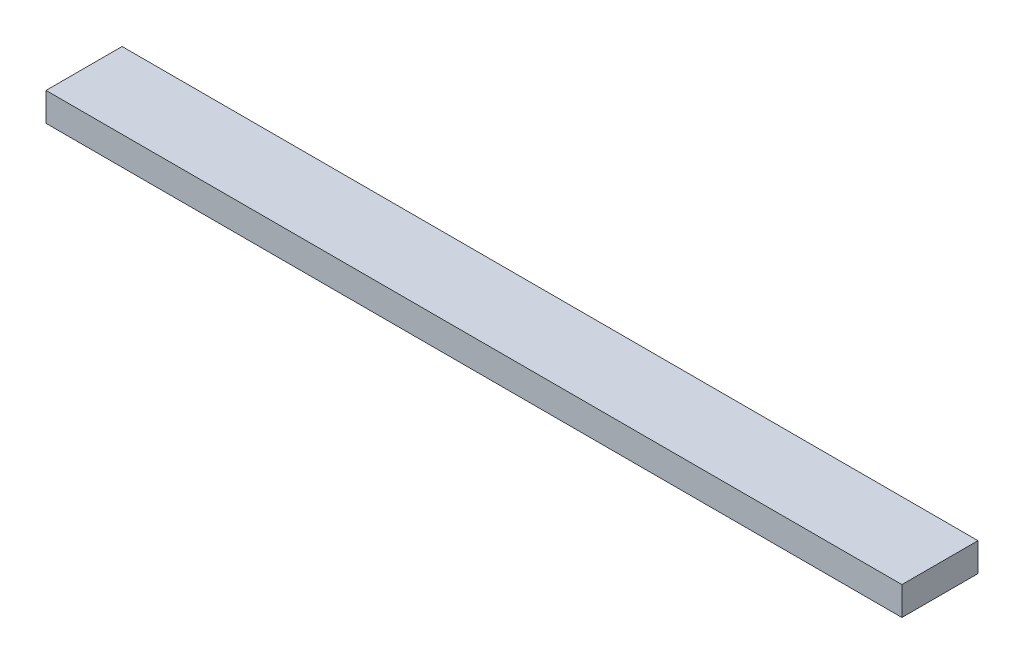
SolidWorks part; units mm, degrees
ref_plane "Front Plane" through (0, 0, 0) normal (0, 0, 1) x (1, 0, 0)
ref_plane "Top Plane" through (0, 0, 0) normal (0, 1, 0) x (1, 0, 0)
ref_plane "Right Plane" through (0, 0, 0) normal (1, 0, 0) x (0, 0, -1)
sketch "Sketch3" plane through (0, 0, 0) normal (0, 1, 0) x (1, 0, 0)
  line L1 (45, -4) -> (-45, -4)
  line L2 (45, -4) -> (45, 4)
  line L3 (45, 4) -> (-45, 4)
  line L4 (-45, -4) -> (-45, 4)
  line L5 (45, -4) -> (-45, 4) construction
  line L6 (45, 4) -> (-45, -4) construction
  point P0 (0, 0)
  dimension "D1" = 8
  dimension "D2" = 90
extrude "Boss-Extrude2" add sketch "Sketch3" along normal blind 3
